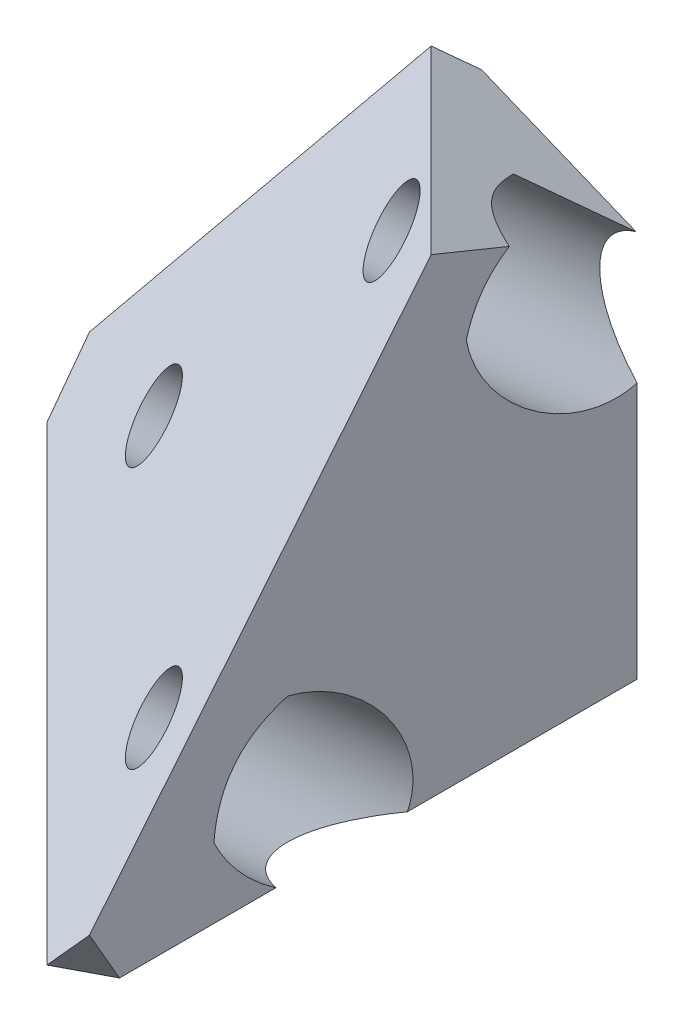
SolidWorks part; units mm, degrees
material "6061-T6 (SS)"
ref_plane "Front Plane" through (0, 0, 0) normal (0, 0, 1) x (1, 0, 0)
ref_plane "Top Plane" through (0, 0, 0) normal (0, 1, 0) x (1, 0, 0)
ref_plane "Right Plane" through (0, 0, 0) normal (1, 0, 0) x (0, 0, -1)
sketch "Sketch1" plane through (0, 0, 0) normal (0, 1, 0) x (1, 0, 0)
  line L0 (-7.7782, 7.7782) -> (7.7782, -7.7782)
  line L1 (-7.7782, 7.7782) -> (7.7782, 7.7782)
  line L2 (7.7782, 7.7782) -> (7.7782, -7.7782)
  dimension "D1" = 22
extrude "Boss-Extrude1" add sketch "Sketch1" along normal blind 14
ref_plane "Plane1" through (0, 0, 0) normal (-0.7071, 0, -0.7071) x (0, -1, 0)
sketch "Sketch2" plane through (0, 0, 0) normal (-0.7071, 0, -0.7071) x (0, -1, 0)
  line L0 (0, 0) -> (-14, -8.0829)
  line L1 (-14, -8.0829) -> (-14, 0)
  line L2 (-14, 0) -> (0, 0)
  dimension "D1" = 30
extrude "Cut-Extrude1" cut sketch "Sketch2" against normal through all both and the other way through all
ref_plane "Plane2" through (7.3485, -6, -7.3485) normal (-0.6124, 0.5, 0.6124) x (0.7906, 0.3873, 0.4743)
sketch "Sketch7" plane through (0, 0, -7.7782) normal (0, 0, -1) x (-1, 0, 0)
  line L4 (-7.7782, 0) -> (7.7782, 0)
  line L5 (7.7782, 0) -> (-3.6528, 14)
  line L6 (-3.6528, 14) -> (-7.7782, 14)
  line L7 (-7.7782, 14) -> (-7.7782, 0)
  line L8 (-7.7782, 0) -> (7.7782, 0)
  line L9 (7.7782, 0) -> (-3.6528, 14)
  line L10 (-3.6528, 14) -> (-7.7782, 14)
  line L11 (-7.7782, 14) -> (-7.7782, 0)
  dimension "D1" = 0
extrude "Boss-Extrude2" add sketch "Sketch7" along normal blind 2
hole_wizard "CSK for M2 Flat Head Machine Screw1" positions "Sketch3" profile "Sketch4" countersink size "M2" standard "ANSI Metric"
sketch "Sketch3" plane through (7.3485, -6, -7.3485) normal (-0.6124, 0.5, 0.6124) x (0.7906, 0.3873, 0.4743)
  line L1 (7.2296, 14.4591) -> (2.4597, 4.9193) construction
  line L2 (6.9318, 1.5652) -> (-2.9069, 6.4846) construction
  line L4 (-9.8387, 4.9193) -> (9.8387, -4.9193) construction
  line L5 (9.8387, 13.1546) -> (4.6204, 15.7637) construction
  point P0 (6.9318, 1.5652)
  point P4 (6.4846, 12.9692)
  point P12 (-2.9069, 6.4846)
  dimension "D1" = 5.5
  dimension "D2" = 10
  dimension "D3" = 4.5
sketch "Sketch4" plane through (12.8285, -2.1029, -5.0504) normal (0.7891, 0.4344, 0.4344) x (-0.0488, 0.7492, -0.6605)
  line L0 (0, 0) -> (0, 13.921)
  line L1 (0, 13.921) -> (1.2, 13.2)
  line L2 (1.2, 13.2) -> (1.2, 11)
  line L3 (1.2, 11) -> (2.2, 10)
  line L4 (2.2, 10) -> (2.2, 0)
  line L6 (2.2, 0) -> (0, 0)
  line L7 (-1.2, 11) -> (-2.2, 10) construction
  line L10 (0, 13.921) -> (-1.2, 13.2) construction
  line L11 (0, -6.35) -> (0, 107.95) construction
  dimension "Hole Dia." = 2.4
  dimension "Hole Depth" = 13.2
  dimension "C'Sink Dia." = 4.4
  dimension "C'Sink Angle" = 90
  dimension "Drill Angle" = 118
  dimension "Head Clearance" = 10
hole_wizard "M2x0.4 Tapped Hole1" positions "Sketch5" profile "Sketch6" tap size "M2x0.4" standard "ANSI Metric"
sketch "Sketch5" plane through (0, 0, -9.7782) normal (0, 0, -1) x (-1, 0, 0)
  line L2 (-7.7782, 7.6299) -> (-7.7782, 0) construction
  line L3 (0.5668, 0) -> (7.7782, 0) construction
  point P0 (-2.7782, 9.5)
  point P2 (-5.7782, 1.5)
  point P4 (3.7218, 1.5)
  dimension "D1" = 1.5
  dimension "D2" = 2
  dimension "D3" = 8
  dimension "D4" = 3
  dimension "D5" = 9.5
sketch "Sketch6" plane through (2.7782, 9.5, -9.7782) normal (1, 0, 0) x (0, 1, 0)
  line L0 (0, 0) -> (0, 3.9807)
  line L1 (0, 3.9807) -> (0.8, 3.5)
  line L2 (0.8, 3.5) -> (0.8, 0.225)
  line L3 (0.8, 0.225) -> (1.025, 0)
  line L5 (1.025, 0) -> (0, 0)
  line L6 (-0.8, 0.225) -> (-1.025, 0) construction
  line L10 (0, 3.9807) -> (-0.8, 3.5) construction
  line L11 (0, -6.35) -> (0, 107.95) construction
  dimension "Tap Drill Dia." = 1.6
  dimension "Tap Drill Depth" = 3.5
  dimension "Near C'Sink Dia." = 2.05
  dimension "Near C'Sink Angle" = 90
  dimension "Drill Angle" = 118
cosmetic thread "Hole Thread1" parameters "D1"=3, "D2"=2
cosmetic thread "Hole Thread3" parameters "D1"=3, "D2"=2
cosmetic thread "Hole Thread4" parameters "D1"=3, "D2"=2
sketch "Sketch11" plane through (0, 0, 0) normal (-0.6124, 0.5, 0.6124) x (0.4743, -0.3873, 0.7906)
  line L4 (-4.6204, 15.7637) -> (-9.463, 15.7637)
  line L5 (-9.463, 15.7637) -> (-11.4198, 13.1546)
  line L6 (-11.4198, 13.1546) -> (-9.8387, 13.1546)
  line L7 (-9.8387, 13.1546) -> (-4.6204, 15.7637)
  line L8 (-4.6204, 15.7637) -> (-9.463, 15.7637)
  line L9 (-9.463, 15.7637) -> (-11.4198, 13.1546)
  line L10 (-11.4198, 13.1546) -> (-9.8387, 13.1546)
  line L11 (-9.8387, 13.1546) -> (-4.6204, 15.7637)
  dimension "D1" = 0
extrude "Boss-Extrude4" [suppressed] add sketch "Sketch11" against normal up to surface (1.2247 mm away)
sketch "Sketch12" plane through (0, 0, 0) normal (-0.6124, 0.5, 0.6124) x (0.4743, -0.3873, 0.7906)
  line L4 (-9.8387, -4.9193) -> (-9.8387, 13.1546)
  line L5 (-9.8387, 13.1546) -> (-11.4198, 13.1546)
  line L6 (-11.4198, 13.1546) -> (-11.4198, -4.9193)
  line L7 (-11.4198, -4.9193) -> (-9.8387, -4.9193)
  line L8 (-9.8387, -4.9193) -> (-9.8387, 13.1546)
  line L9 (-9.8387, 13.1546) -> (-11.4198, 13.1546)
  line L10 (-11.4198, 13.1546) -> (-11.4198, -4.9193)
  line L11 (-11.4198, -4.9193) -> (-9.8387, -4.9193)
  dimension "D1" = 0
extrude "Boss-Extrude5" add sketch "Sketch12" against normal up to surface (1.2247 mm away)
sketch "Sketch9" plane through (0, 0, 0) normal (-0.6124, 0.5, 0.6124) x (0.4743, -0.3873, 0.7906)
  line L0 (8.2387, 6.1193) -> (8.0498, 4.0249)
  line L1 (-4.6204, 15.7637) -> (9.8387, 4.9193) construction
  line L2 (-9.8387, -4.9193) -> (9.8387, 4.9193) construction
  line L3 (8.0498, 4.0249) -> (9.8387, 4.9193)
  line L4 (9.8387, 4.9193) -> (8.2387, 6.1193)
  line L5 (-9.631, -4.8155) -> (-11.4198, -5.7099)
  line L6 (-11.4198, -5.7099) -> (-11.4198, -3.7099)
  line L7 (-11.4198, -3.7099) -> (-9.631, -4.8155)
  line L8 (-9.631, -4.8155) -> (-9.9137, -4.963)
  line L10 (-11.4198, 13.1546) -> (-11.4198, -4.9193) construction
  line L11 (-4.6204, 15.7637) -> (-11.4198, 12.364)
  line L12 (-11.4198, 12.364) -> (-11.4198, 20.8633)
  line L13 (-11.4198, 20.8633) -> (-4.6204, 15.7637)
  line L14 (-4.6204, 15.7637) -> (-9.8387, 13.1546) construction
  dimension "D1" = 2
extrude "Cut-Extrude3" cut sketch "Sketch9" against normal through all both and the other way through all contours L5 L6 L7 | L0 L3 L4 | L12 L13 L11
